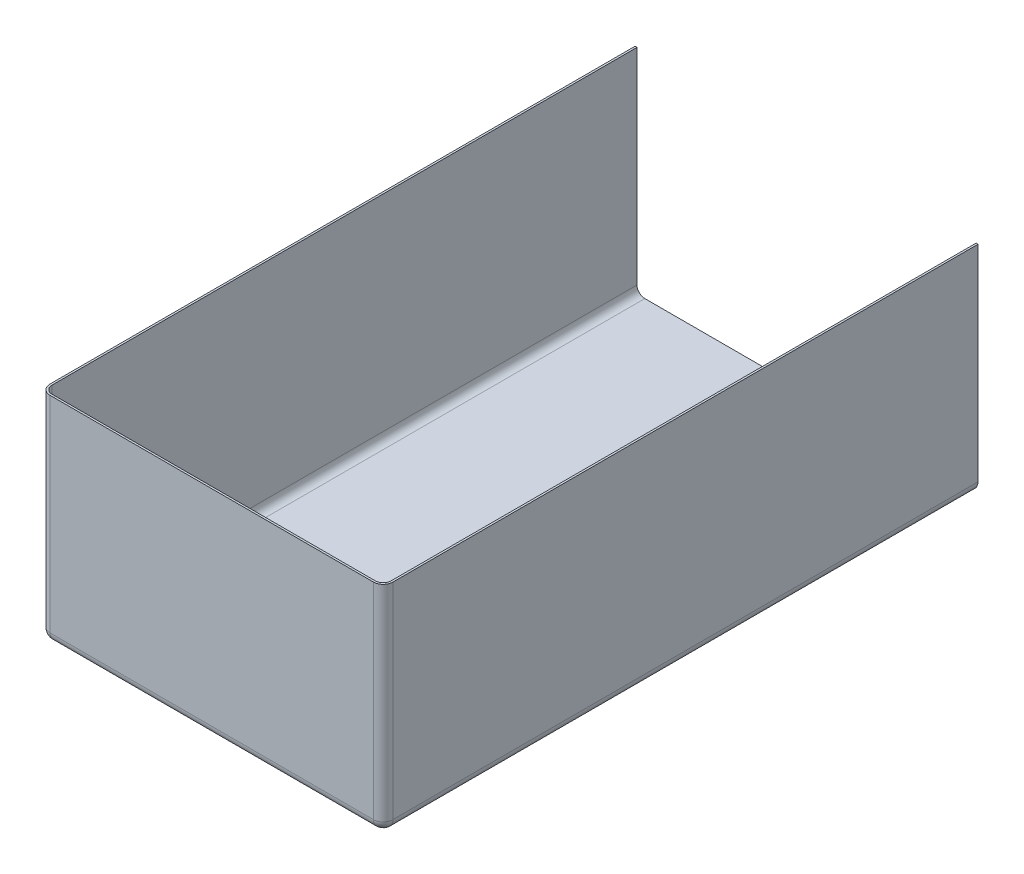
SolidWorks part; units mm, degrees
ref_plane "前视基准面" through (0, 0, 0) normal (0, 0, 1) x (1, 0, 0)
ref_plane "上视基准面" through (0, 0, 0) normal (0, 1, 0) x (1, 0, 0)
ref_plane "右视基准面" through (0, 0, 0) normal (1, 0, 0) x (0, 0, -1)
other "Configuration Table"
sketch "草图1" plane through (0, 0, 0) normal (0, 0, 1) x (1, 0, 0)
  line L1 (-175, 110) -> (175, 110)
  line L2 (-175, 110) -> (-175, -110)
  line L3 (-175, -110) -> (175, -110)
  line L4 (175, 110) -> (175, -110)
  line L5 (-175, 110) -> (175, -110) construction
  line L6 (-175, -110) -> (175, 110) construction
  point P0 (0, 0)
  dimension "D1" = 350
  dimension "D2" = 220
extrude "凸台-拉伸1" add sketch "草图1" along normal blind 607
fillet "圆角1" radius 10 5 edges at (175, 0, 607) (-175, -110, 303.5) (0, -110, 607) (175, -110, 303.5) (-175, 0, 607)
shell "抽壳1" thickness 2
